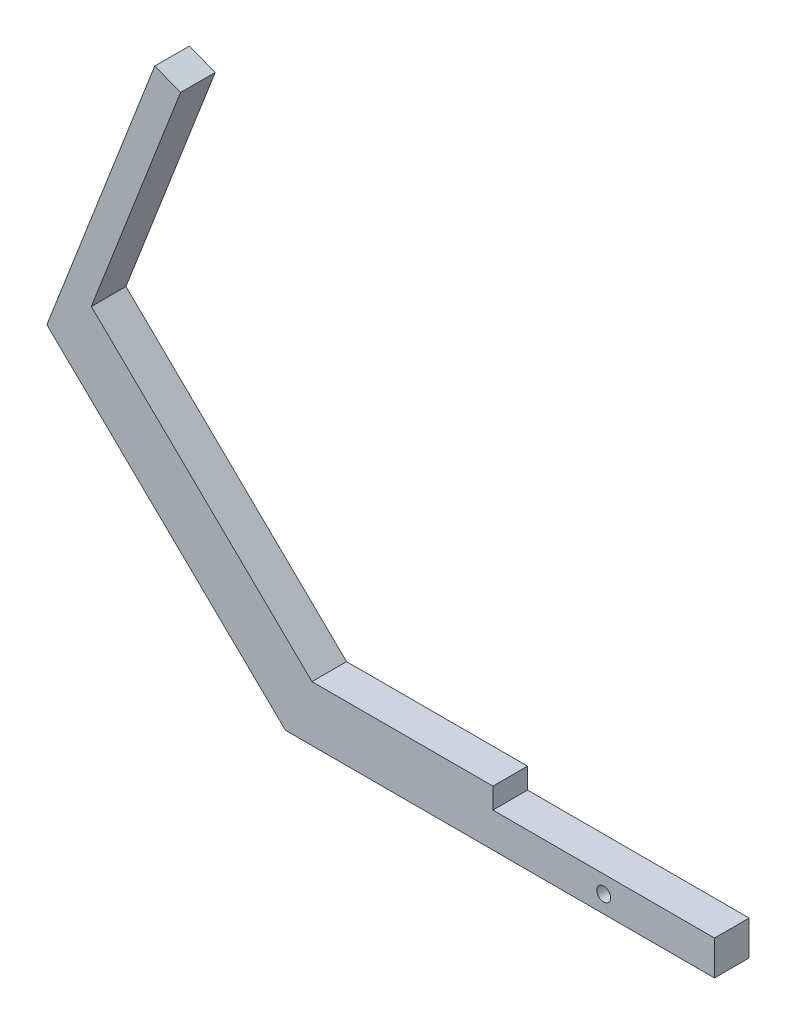
SolidWorks part; units mm, degrees
ref_plane "前视基准面" through (0, 0, 0) normal (0, 0, 1) x (1, 0, 0)
ref_plane "上视基准面" through (0, 0, 0) normal (0, 1, 0) x (1, 0, 0)
ref_plane "右视基准面" through (0, 0, 0) normal (1, 0, 0) x (0, 0, -1)
sketch "草图1" plane through (0, 0, 0) normal (0, 0, 1) x (1, 0, 0)
  line L0 (0, 0) -> (0, -40)
  line L1 (0, -40) -> (-149.8411, -40)
  line L2 (-149.8411, -40) -> (-322.0729, 127.4817)
  line L3 (-322.0729, 127.4817) -> (-244.1689, 328.224)
  line L4 (-244.1689, 328.224) -> (-225.5237, 320.9882)
  line L5 (-225.5237, 320.9882) -> (-289.9763, 154.9076)
  line L6 (0, 0) -> (-130.6752, 0)
  line L7 (-130.6752, 0) -> (-289.9763, 154.9076)
  dimension "D1" = 40
  dimension "D2" = 166.0806
  dimension "D3" = 20
extrude "凸台-拉伸2" add sketch "草图1" along normal blind 25
sketch "草图3" plane through (0, 0, 0) normal (0, 0, -1) x (-1, 0, 0)
  line L0 (0, -40) -> (-160, -40)
  line L1 (0, -15) -> (-160, -15)
  line L2 (0, -40) -> (0, 0) construction
  line L3 (-160, -15) -> (-160, -40)
  circle A0 centre (-80, -27.5) radius 5
  line M6 (0, 0) -> (0, -40)
  dimension "D3" = 10
  dimension "D1" = 25
  dimension "D2" = 160
  dimension "D4" = 80
extrude "凸台-拉伸3" add sketch "草图3" against normal blind 25 contours L1 L3 L0 A0 M6
